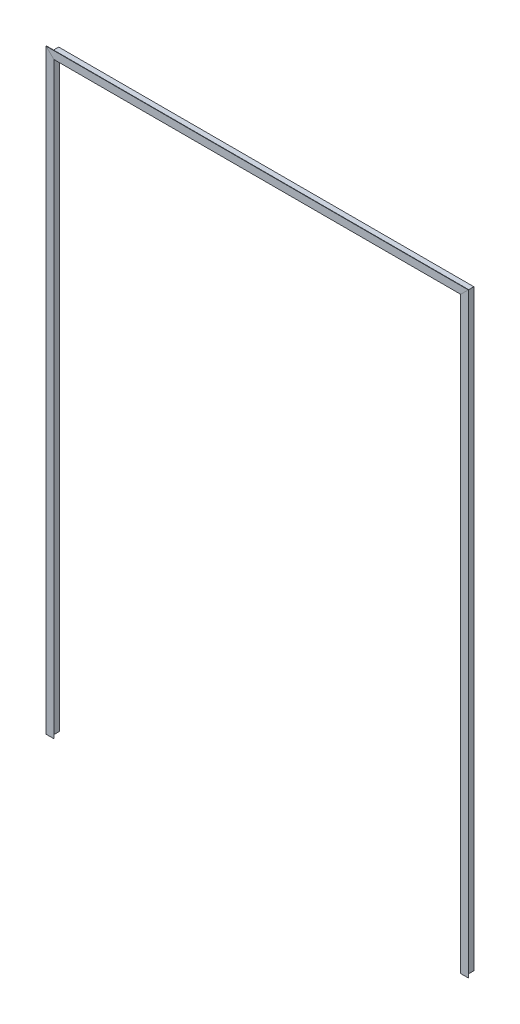
SolidWorks part; units mm, degrees
material "ASTM A36 Steel"
ref_plane "Front Plane" through (0, 0, 0) normal (0, 0, 1) x (1, 0, 0)
ref_plane "Top Plane" through (0, 0, 0) normal (0, 1, 0) x (1, 0, 0)
ref_plane "Right Plane" through (0, 0, 0) normal (1, 0, 0) x (0, 0, -1)
sketch "Sketch1" plane through (0, 0, 0) normal (0, 0, 1) x (1, 0, 0)
  line L0 (0, 0) -> (0, 10000)
  line L1 (0, 10000) -> (7000, 10000)
  line L2 (7000, 10000) -> (7000, 0)
  dimension "D1" = 10000
  dimension "D2" = 7000
other "St section ST6X17.5(1)"
ref_plane "Plane1" through (0, 0, 0) normal (0, 1, 0) x (-1, 0, 0)
sketch "Sketch11" plane through (0, 0, 0) normal (0, 1, 0) x (-1, 0, 0)
  line L0 (-64.4906, 152.4) -> (64.4906, 152.4)
  line L2 (-5.4356, 0) -> (-5.4356, 123.952)
  line L3 (-14.9864, 135.2265) -> (-60.0336, 142.7349)
  line L5 (-64.4906, 152.4) -> (-64.4906, 147.9963)
  line L6 (64.4906, 152.4) -> (64.4906, 147.9963)
  line L7 (60.0336, 142.7349) -> (14.9864, 135.2265)
  line L8 (5.4356, 123.952) -> (5.4356, 0)
  line L9 (64.4906, 138.557) -> (-64.4906, 138.557) construction
  line L12 (-5.4356, 0) -> (5.4356, 0)
  arc A0 (-60.0336, 142.7349) -> (-64.4906, 147.9963) centre (-59.1566, 147.9963) cw
  arc A1 (-5.4356, 123.952) -> (-14.9864, 135.2265) centre (-16.8656, 123.952) ccw
  arc A2 (14.9864, 135.2265) -> (5.4356, 123.952) centre (16.8656, 123.952) ccw
  arc A3 (60.0336, 142.7349) -> (64.4906, 147.9963) centre (59.1566, 147.9963) ccw
  point P9 (0, 152.4)
  point P18 (0, 33.9014)
  point P20 (-5.4356, 61.976)
  point P22 (5.4356, 61.976)
  point P23 (0, 0)
  point P24 (0, 0)
  dimension "RI" = 11.43
  dimension "D2" = 9.463
  dimension "RA" = 5.334
  dimension "D1" = 123.952
  dimension "TW" = 10.8712
  dimension "BF" = 128.9812
  dimension "DEPTH" = 152.4
  dimension "TF" = 13.843
  dimension "delta" = 59.055
